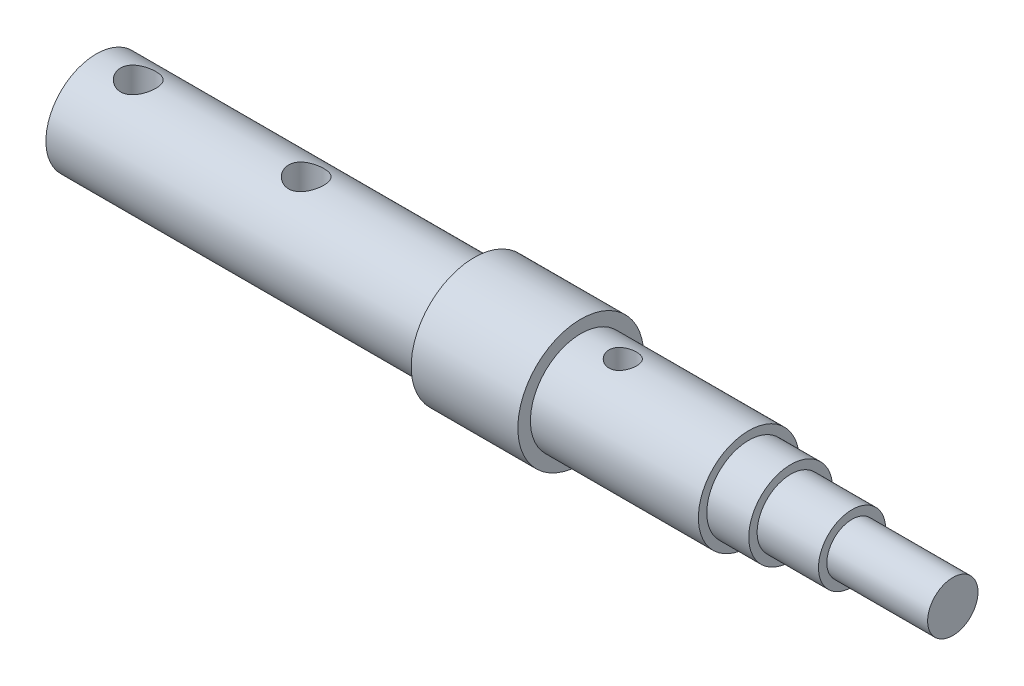
SolidWorks part; units mm, degrees
material "5052-H34"
ref_plane "正面" through (0, 0, 0) normal (0, 0, 1) x (1, 0, 0)
ref_plane "平面" through (0, 0, 0) normal (0, 1, 0) x (1, 0, 0)
ref_plane "右側面" through (0, 0, 0) normal (1, 0, 0) x (0, 0, -1)
sketch "ｽｹｯﾁ1" plane through (0, 0, 0) normal (1, 0, 0) x (0, 0, -1)
  circle A0 centre (0, 0) radius 6
  dimension "D1" = 12
extrude "ﾎﾞｽ - 押し出し1" add sketch "ｽｹｯﾁ1" along normal blind 45
sketch "ｽｹｯﾁ2" plane through (45, 0, 0) normal (1, 0, 0) x (0, 0, -1)
  circle A0 centre (0, 0) radius 7.5
  dimension "D1" = 15
extrude "ﾎﾞｽ - 押し出し2" add sketch "ｽｹｯﾁ2" along normal blind 12.7
sketch "ｽｹｯﾁ3" plane through (57.7, 0, 0) normal (1, 0, 0) x (0, 0, -1)
  circle A0 centre (0, 0) radius 6
  dimension "D1" = 12
extrude "ﾎﾞｽ - 押し出し3" add sketch "ｽｹｯﾁ3" along normal blind 20
sketch "ｽｹｯﾁ4" plane through (77.7, 0, 0) normal (1, 0, 0) x (0, 0, -1)
  circle A0 centre (0, 0) radius 5
  dimension "D1" = 10
extrude "ﾎﾞｽ - 押し出し4" add sketch "ｽｹｯﾁ4" along normal blind 5
sketch "ｽｹｯﾁ5" plane through (82.7, 0, 0) normal (1, 0, 0) x (0, 0, -1)
  circle A0 centre (0, 0) radius 4
  dimension "D1" = 8
extrude "ﾎﾞｽ - 押し出し5" add sketch "ｽｹｯﾁ5" along normal blind 7.3
sketch "ｽｹｯﾁ6" plane through (90, 0, 0) normal (1, 0, 0) x (0, 0, -1)
  circle A0 centre (0, 0) radius 3
  dimension "D1" = 6
extrude "ﾎﾞｽ - 押し出し6" add sketch "ｽｹｯﾁ6" along normal blind 12
sketch "ｽｹｯﾁ7" plane through (0, 0, 0) normal (0, 1, 0) x (1, 0, 0)
  line L0 (0, 0) -> (25, 0) construction
  circle A0 centre (25, 0) radius 2.1
  circle A1 centre (5, 0) radius 2.1
  dimension "D1" = 4.2
  dimension "D2" = 5
  dimension "D3" = 20
extrude "ｶｯﾄ - 押し出し1" cut sketch "ｽｹｯﾁ7" against normal through all both and the other way through all
sketch "ｽｹｯﾁ8" plane through (0, 0, 0) normal (0, 1, 0) x (1, 0, 0)
  line L0 (57.7, 0) -> (62.7, 0) construction
  line L1 (57.7, -6) -> (57.7, 6) construction
  circle A0 centre (62.7, 0) radius 1.65
  dimension "D1" = 3.3
  dimension "D2" = 5
extrude "ｶｯﾄ - 押し出し2" cut sketch "ｽｹｯﾁ8" against normal through all both and the other way through all
